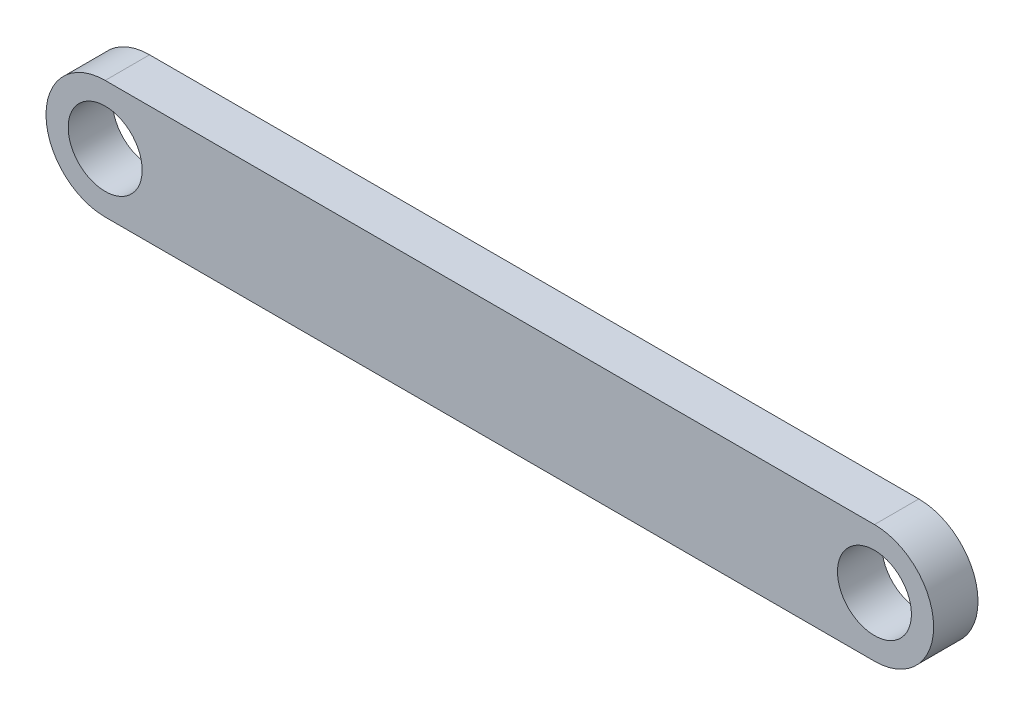
SolidWorks part; units mm, degrees
material "ABS"
ref_plane "Front Plane" through (0, 0, 0) normal (0, 0, 1) x (1, 0, 0)
ref_plane "Top Plane" through (0, 0, 0) normal (0, 1, 0) x (1, 0, 0)
ref_plane "Right Plane" through (0, 0, 0) normal (1, 0, 0) x (0, 0, -1)
sketch "Sketch1" plane through (0, 0, 0) normal (0, 0, 1) x (1, 0, 0)
  line L0 (0, 0) -> (-52, 0)
  dimension "D1" = 52
sketch "Sketch2" plane through (0, 0, 0) normal (0, 0, 1) x (1, 0, 0)
  line L0 (-52, 4) -> (0, 4)
  line L1 (-52, -4) -> (0, -4)
  circle A0 centre (-52, 0) radius 2.5
  circle A1 centre (0, 0) radius 2.5
  arc A2 (-52, 4) -> (-52, -4) centre (-52, 0) ccw
  arc A3 (0, -4) -> (0, 4) centre (0, 0) ccw
  dimension "D1" = 5
  dimension "D2" = 8
  dimension "D3" = 5
  dimension "D4" = 8
extrude "Boss-Extrude1" add sketch "Sketch2" along normal blind 3
